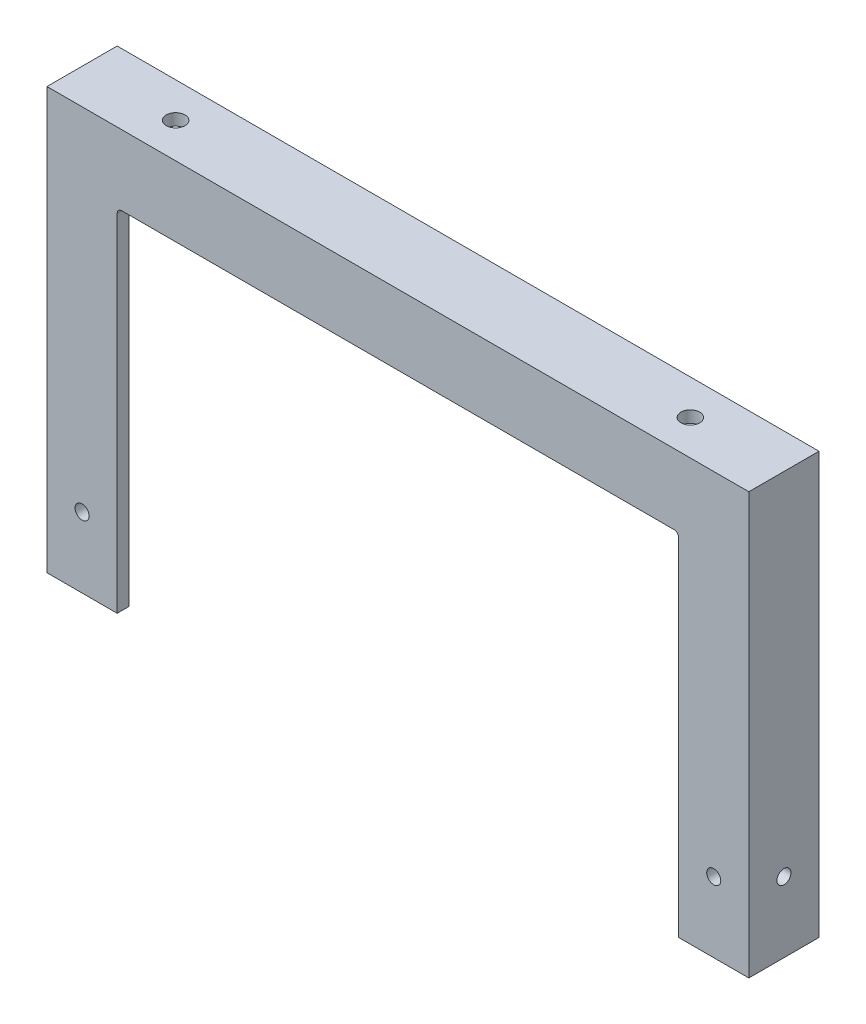
SolidWorks part; units mm, degrees
material "1023 Carbon Steel Sheet (SS)"
ref_plane "Front Plane" through (0, 0, 0) normal (0, 0, 1) x (1, 0, 0)
ref_plane "Top Plane" through (0, 0, 0) normal (0, 1, 0) x (1, 0, 0)
ref_plane "Right Plane" through (0, 0, 0) normal (1, 0, 0) x (0, 0, -1)
sketch "Sketch1" plane through (0, 0, 0) normal (0, 0, 1) x (1, 0, 0)
  line L0 (0, 0) -> (0, 180)
  line L1 (0, 180) -> (300, 180)
  line L2 (300, 180) -> (300, 0)
  line L3 (300, 0) -> (270, 0)
  line L4 (270, 0) -> (270, 150)
  line L5 (270, 150) -> (30, 150)
  line L6 (30, 150) -> (30, 0)
  line L7 (30, 0) -> (0, 0)
  dimension "D1" = 300
  dimension "D2" = 240
  dimension "D3" = 180
extrude "Boss-Extrude1" add sketch "Sketch1" along normal blind 25
sketch "Sketch3" plane through (0, 0, 0) normal (0, 0, -1) x (-1, 0, 0)
  line L0 (0, 0) -> (-5, 0) construction
  line L1 (0, 0) -> (-30, 0) construction
  line L2 (-5, 0) -> (-30, 0)
  line L3 (-30, 0) -> (-30, 150)
  line L4 (-30, 150) -> (-270, 150)
  line L5 (-270, 150) -> (-270, 0)
  line L6 (-270, 0) -> (-295, 0)
  line L7 (-270, 0) -> (-300, 0) construction
  line L8 (-295, 0) -> (-295, 175)
  line L9 (-295, 175) -> (-5, 175)
  line L10 (-5, 175) -> (-5, 0)
extrude "Cut-Extrude2" cut sketch "Sketch3" against normal blind 20
sketch "Sketch6" plane through (0, 0, 25) normal (0, 0, 1) x (1, 0, 0)
  line L0 (15, 0) -> (15, 30) construction
  line L1 (0, 0) -> (30, 0) construction
  line L2 (285, 0) -> (285, 30) construction
  line L3 (270, 0) -> (300, 0) construction
  circle A0 centre (15, 30) radius 3
  circle A1 centre (285, 30) radius 3
extrude "Cut-Extrude5" cut sketch "Sketch6" against normal blind 400
sketch "Sketch7" plane through (0, 0, 0) normal (0, 0, -1) x (-1, 0, 0)
  line L0 (-300, 0) -> (-300, 180)
  line L1 (-300, 180) -> (0, 180)
  line L2 (0, 180) -> (0, 0)
  line L3 (0, 0) -> (-5, 0)
  line L4 (-5, 0) -> (-5, 175)
  line L5 (-5, 175) -> (-295, 175)
  line L6 (-295, 175) -> (-295, 0)
  line L7 (-295, 0) -> (-300, 0)
extrude "Boss-Extrude2" add sketch "Sketch7" along normal blind 5
sketch "Sketch8" plane through (0, 0, 0) normal (-1, 0, 0) x (0, 0, 1)
  line L0 (10, 0) -> (10, 30) construction
  line L1 (25, 0) -> (-5, 0) construction
  circle A0 centre (10, 30) radius 3
extrude "Cut-Extrude6" cut sketch "Sketch8" against normal blind 350
fillet "Fillet3" radius 2 7 edges at (270, 150, 22.5) (30, 150, 22.5) (5, 175, 7.5) (5, 87.5, 20) (295, 87.5, 20) (295, 175, 7.5) (150, 175, 20)
sketch "Sketch9" plane through (0, 180, 0) normal (0, 1, 0) x (1, 0, 0)
  line L0 (0, -10) -> (40, -10) construction
  line L1 (0, -25) -> (0, 5) construction
  line L2 (300, -10) -> (260, -10) construction
  line L3 (300, -25) -> (300, 5) construction
  circle A0 centre (40, -10) radius 4
  circle A1 centre (260, -10) radius 4
extrude "Cut-Extrude7" cut sketch "Sketch9" against normal blind 350
